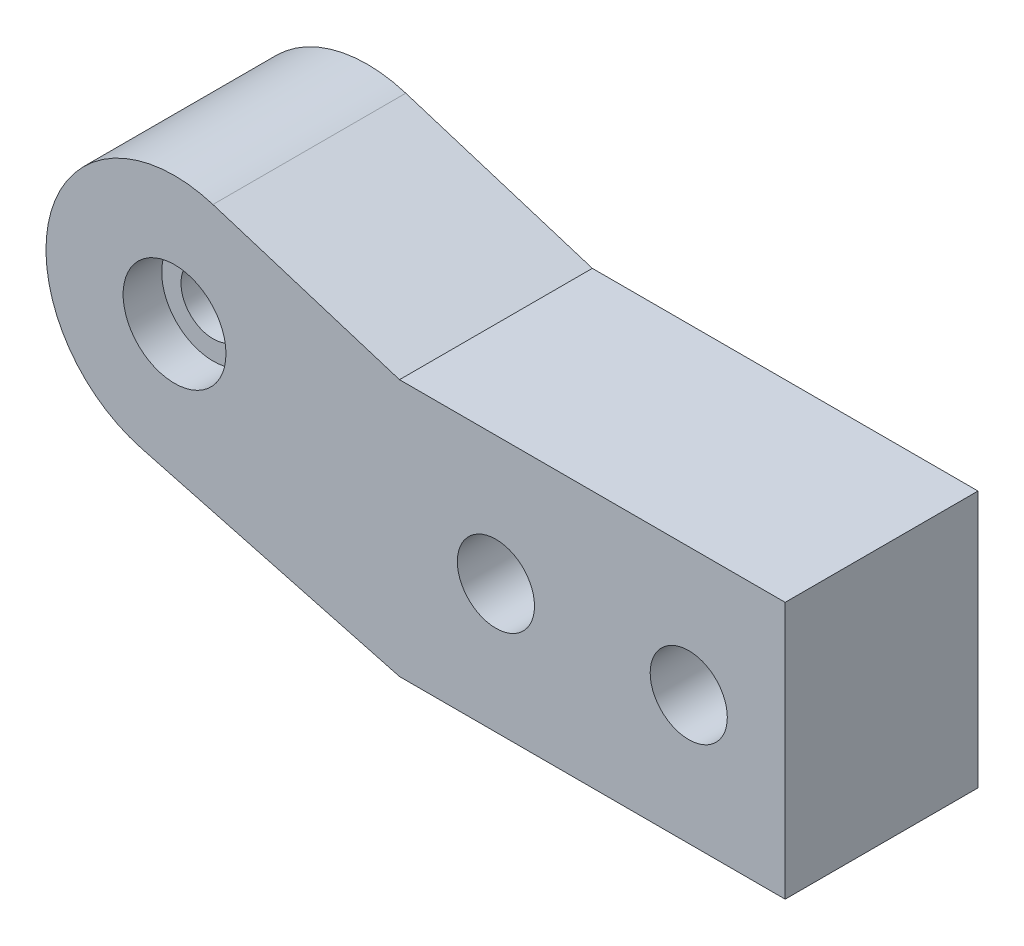
SolidWorks part; units mm, degrees
ref_plane "前视基准面" through (0, 0, 0) normal (0, 0, 1) x (1, 0, 0)
ref_plane "上视基准面" through (0, 0, 0) normal (0, 1, 0) x (1, 0, 0)
ref_plane "右视基准面" through (0, 0, 0) normal (1, 0, 0) x (0, 0, -1)
other "Configuration Table"
sketch "草图1" plane through (0, 0, 0) normal (0, 0, 1) x (1, 0, 0)
  line L0 (-30, 0) -> (0, 0)
  line L1 (0, 0) -> (0, -20)
  line L2 (0, -20) -> (-30, -20)
  line L3 (0, -10) -> (-50000, -10) construction
  line L5 (-47.5, -1.2569) -> (-47.5, -50001.2569) construction
  line L6 (-30, 0) -> (-44.5124, 4.5433)
  line L7 (-30, -20) -> (-50.0694, -14.6643)
  line L8 (-30, 0) -> (-30, -20) construction
  circle A1 centre (-22.5, -10) radius 3
  circle A2 centre (-7.5, -10) radius 3
  arc A3 (-44.5124, 4.5433) -> (-50.0694, -14.6643) centre (-47.5, -5) ccw
  point P17 (0, -10)
  dimension "D1" = 6
  dimension "D2" = 6
  dimension "D7" = 20
  dimension "D3" = 15
  dimension "D4" = 7.5
  dimension "D5" = 30
  dimension "D6" = 20
  dimension "D8" = 25
  dimension "D9" = 5
extrude "凸台-拉伸1" add sketch "草图1" along normal blind 15
sketch "草图4" plane through (0, 0, 0) normal (0, 0, -1) x (-1, 0, 0)
  circle A0 centre (7.5, -10) radius 5
  circle A1 centre (22.5, -10) radius 5
  dimension "D1" = 10
  dimension "D2" = 10
extrude "切除-拉伸3" cut sketch "草图4" against normal blind 6
sketch "草图8" plane through (0, 0, 15) normal (0, 0, 1) x (1, 0, 0)
  circle A0 centre (-47.5, -5) radius 4
  dimension "D1" = 8
extrude "切除-拉伸4" cut sketch "草图8" against normal blind 3
sketch "草图10" plane through (0, 0, 12) normal (0, 0, 1) x (1, 0, 0)
  circle A0 centre (-47.5, -5) radius 2.5
  dimension "D1" = 5
extrude "切除-拉伸5" cut sketch "草图10" against normal blind 13
